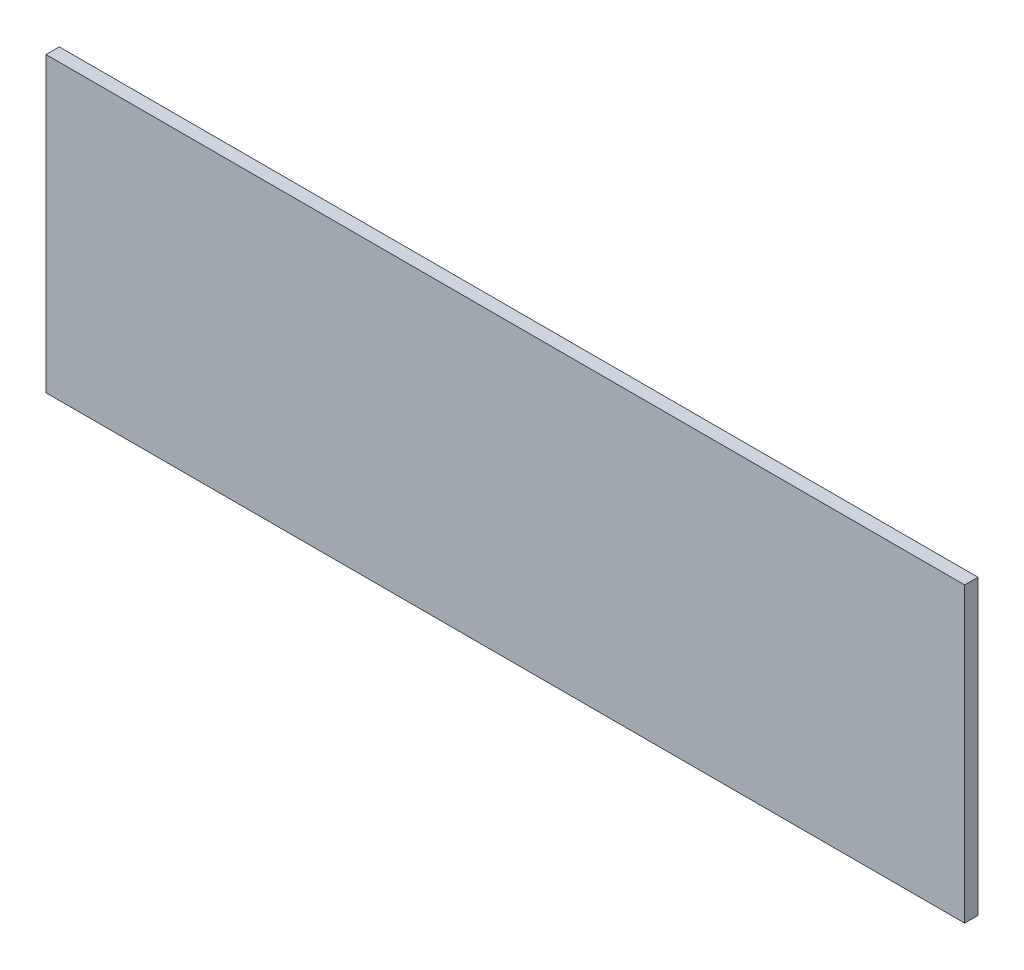
SolidWorks part; units mm, degrees
ref_plane "Front Plane" through (0, 0, 0) normal (1, 0, 0) x (0, 1, 0)
ref_plane "Top Plane" through (0, 0, 0) normal (0, 0, 1) x (0, 1, 0)
ref_plane "Right Plane" through (0, 0, 0) normal (0, 1, 0) x (-1, 0, 0)
sketch "Sketch1" plane through (0, 0, 0) normal (0, 0, 1) x (0, 1, 0)
  line L1 (0, 0) -> (110, 0)
  line L2 (0, 0) -> (0, 345)
  line L3 (0, 345) -> (110, 345)
  line L4 (110, 0) -> (110, 345)
  dimension "D1" = 345
  dimension "D2" = 110
extrude "Boss-Extrude1" add sketch "Sketch1" along normal blind 5 contours L3 L4 L1 L2
